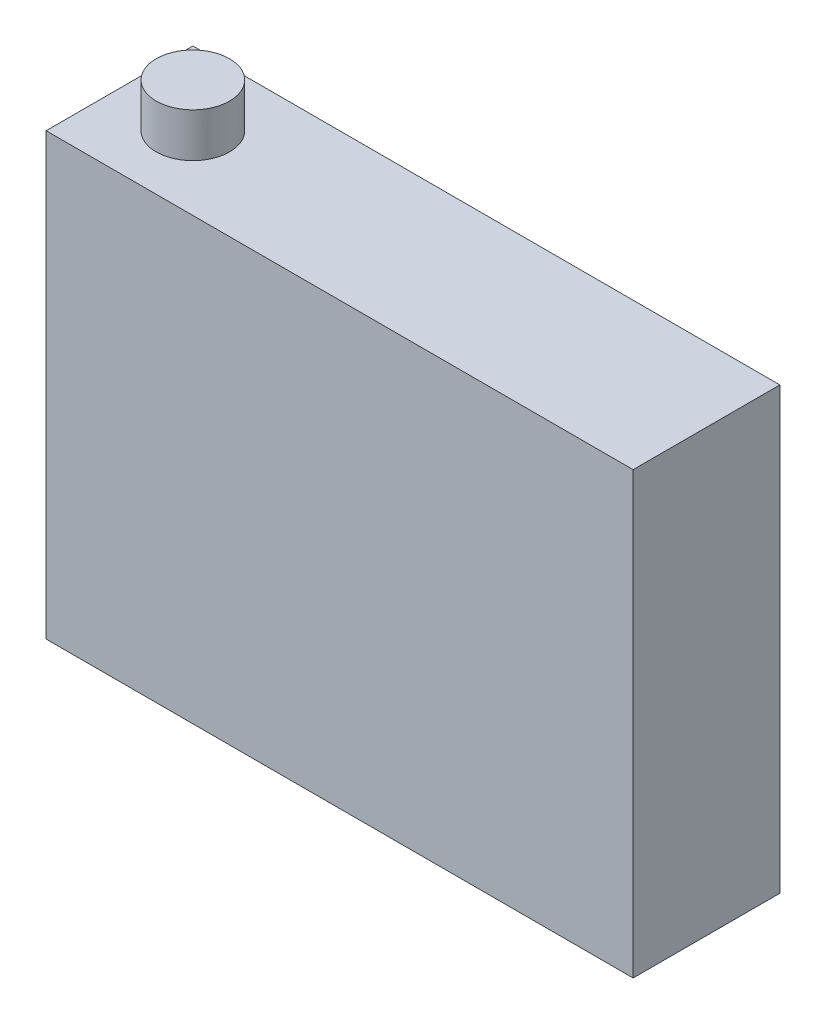
SolidWorks part; units mm, degrees
ref_plane "Plan de face" through (0, 0, 0) normal (0, 0, 1) x (1, 0, 0)
ref_plane "Plan de dessus" through (0, 0, 0) normal (0, 1, 0) x (1, 0, 0)
ref_plane "Plan de droite" through (0, 0, 0) normal (1, 0, 0) x (0, 0, -1)
sketch "Esquisse1" plane through (0, 0, 0) normal (0, 1, 0) x (1, 0, 0)
  line L1 (0, 0) -> (-40, 0)
  line L2 (0, 0) -> (0, -10)
  line L3 (0, -10) -> (-40, -10)
  line L4 (-40, 0) -> (-40, -10)
  dimension "D1" = 10
  dimension "D2" = 40
extrude "Boss.-Extru.1" add sketch "Esquisse1" along normal blind 30
sketch "Esquisse2" plane through (0, 30, 0) normal (0, 1, 0) x (1, 0, 0)
  line L0 (-40, -5) -> (0, -5) construction
  line L1 (-40, 0) -> (-40, -10) construction
  line L2 (0, -10) -> (0, 0) construction
  circle A0 centre (-35, -5) radius 2.5
  dimension "D1" = 5
  dimension "D2" = 5
extrude "Boss.-Extru.2" add sketch "Esquisse2" along normal blind 3
